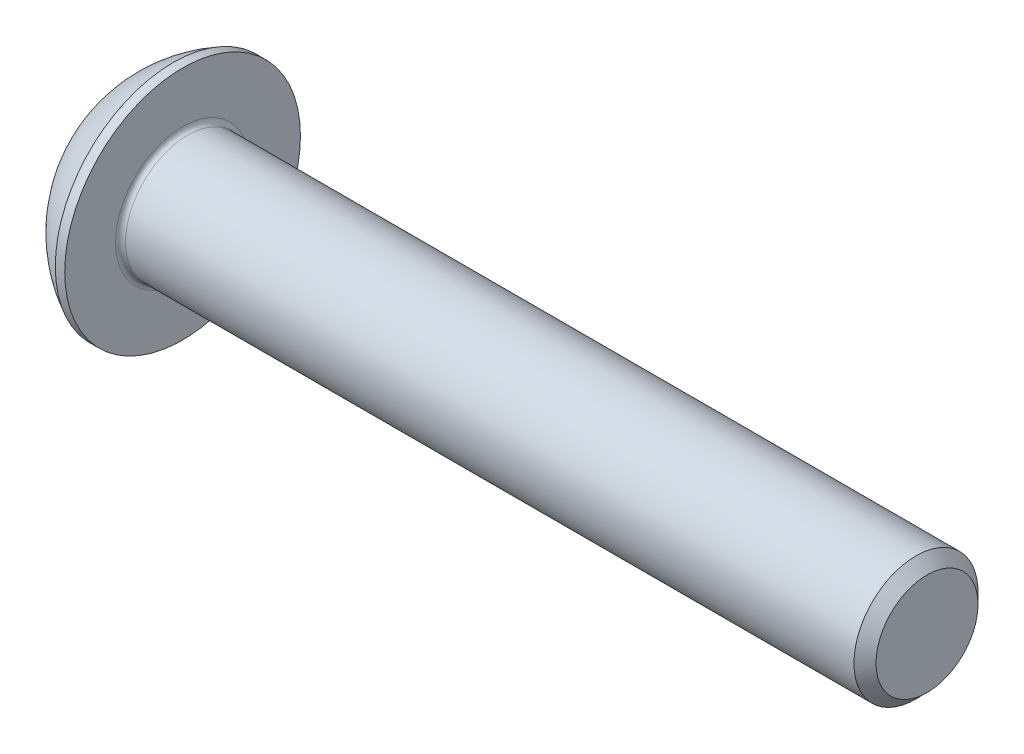
SolidWorks part; units mm, degrees
ref_plane "Plane1" through (0, 0, 0) normal (0, 0, 1) x (1, 0, 0)
ref_plane "Plane2" through (0, 0, 0) normal (0, 1, 0) x (1, 0, 0)
ref_plane "Plane3" through (0, 0, 0) normal (1, 0, 0) x (0, 0, -1)
other "Configuration Table"
sketch "BodySke" plane through (0, 0, 0) normal (0, 0, 1) x (1, 0, 0)
  line L0 (32.75, 0) -> (32.75, 2.055)
  line L1 (32.305, 2.5) -> (2.75, 2.5)
  line L2 (2.75, 2.5) -> (2.75, 4.75)
  line L3 (2.75, 4.75) -> (2.37, 4.75)
  line L4 (0, 0) -> (101.6, 0) construction
  line L5 (2.75, -4.75) -> (2.37, -4.75) construction
  line L6 (55.6768, -2.5) -> (2.75, -2.5) construction
  line L7 (32.75, 0) -> (0, 0)
  line L8 (0, 2.375) -> (0, -2.375) construction
  line L9 (0, 0) -> (0, 2.375)
  line L10 (32.75, 2.055) -> (32.305, 2.5)
  line L11 (32.75, -2.055) -> (32.305, -2.5) construction
  line L12 (3.55, 9.525) -> (3.55, -2.5) construction
  line L13 (2.75, 9.525) -> (2.75, -2.5) construction
  arc A1 (0, 2.375) -> (2.37, 4.75) centre (4.755, 0) cw
  dimension "Diameter" = 5
  dimension "Length" = 30
  dimension "Head_dia" = 9.5
  dimension "D1" = 4.75
  dimension "Head_ht" = 2.75
  dimension "Head_side_ht" = 0.38
  dimension "Minor_dia" = 4.11
  dimension "Body_ch_ang" = 45
  dimension "Advance" = 0.8
  dimension "Thread_nom" = 30
revolve "BaseBody" add sketch "BodySke" angle 360 about L4
cosmetic thread "ThreadCosmetic" [suppressed] parameters "Thread_length"=28.4, "Thread_minor"=4.11
fillet "Fillet1" radius 0.2 1 edges at (2.75, 0, 2.5)
sketch "Sketch2" plane through (0, 0, 0) normal (0, 0, 1) x (1, 0, 0)
  line L0 (0, 1.5) -> (1.56, 1.5)
  line L1 (1.56, 1.5) -> (2.426, 0)
  line L3 (2.426, 0) -> (0, 0)
  line L4 (0, 0) -> (0, 1.5)
  line L5 (0, -1.5) -> (1.56, -1.5) construction
  line L6 (0, 0) -> (47.625, 0) construction
  dimension "D2" = 60
  dimension "PreBroach_depth" = 1.56
  dimension "PreBroach_dia" = 3
revolve "PreBroach" cut sketch "Sketch2" angle 360 about L6
sketch "Sketch3" plane through (0, 0, 0) normal (1, 0, 0) x (0, 0, -1)
  line L0 (-1.5, -0.866) -> (-1.5, 0.866)
  line L1 (-1.5, 0.866) -> (0, 1.7321)
  line L2 (0, 1.7321) -> (1.5, 0.866)
  line L3 (1.5, 0.866) -> (1.5, -0.866)
  line L4 (1.5, -0.866) -> (0, -1.7321)
  line L5 (0, -1.7321) -> (-1.5, -0.866)
  dimension "Hex_size" = 3
  dimension "D3" = 3
  dimension "D1" = 1.5
  dimension "D2" = 1.5
extrude "Hex" cut sketch "Sketch3" along normal blind 1.56
sketch "ThdSchSke" plane through (0, 0, 0) normal (0, 0, 1) x (1, 0, 0)
  line L0 (4.35, -2.055) -> (4.0384, -2.5)
  line L1 (4.35, -2.055) -> (4.6616, -2.5)
  line L2 (4.6616, -2.5) -> (4.6616, -3.125)
  line L3 (-3.175, 0) -> (5.1513, 0) construction
  line L5 (4.6616, -3.125) -> (4.0384, -3.125)
  line L6 (4.0384, -3.125) -> (4.0384, -2.5)
  dimension "Diameter" = 5
  dimension "Thread_minor" = 4.11
  dimension "SideAngle" = 55
  dimension "VeeAngle" = 70
  dimension "Overcut" = 6.25
  dimension "Start" = 4.35
revolve "ThreadSchematic" [suppressed] cut sketch "ThdSchSke" angle 360 about L3
pattern_linear "ThdSchPat" [suppressed]
equation "\"D1@BodySke\" = \"Head_dia@BodySke\" * .5"
equation "\"Thread_minor@ThreadCosmetic\" = \"Minor_dia@BodySke\""
equation "\"D1@Sketch3\" = \"Hex_size@Sketch3\" / 2"
equation "\"D2@Sketch3\" = \"D1@Sketch3\""
equation "\"D3@Sketch3\" = \"Hex_size@Sketch3\""
equation "\"Thread_length@ThreadCosmetic\" = ((sgn( (\"Length@BodySke\" - \"Advance@BodySke\" * 2.0) - \"Thread_nom@BodySke\" )-1)*( (\"Length@BodySke\" - \"Advance@BodySke\" * 2.0) - \"Thread_nom@BodySke\" ))/-2+ \"Thread_nom@BodySke\""
equation "\"Thread_minor@ThdSchSke\" = \"Minor_dia@BodySke\""
equation "\"Diameter@ThdSchSke\" = \"Diameter@BodySke\""
equation "\"Overcut@ThdSchSke\" = \"Diameter@BodySke\" * 1.25"
equation "\"Start@ThdSchSke\" = \"Head_ht@BodySke\" + \"Length@BodySke\" - \"Thread_length@ThreadCosmetic\"  '---Non-countersunk---"
equation "\"Num_threads@ThdSchPat\" = int( \"Thread_length@ThreadCosmetic\" / \"Advance@BodySke\" + 0.999 )  + 1"
equation "\"Advance@ThdSchPat\" = \"Thread_length@ThreadCosmetic\" /  (\"Num_threads@ThdSchPat\" - 1) 'relax it"
equation "\"Num_threads@ThdSchPat\" = \"Num_threads@ThdSchPat\" - sgn( \"Num_threads@ThdSchPat\" - 1) '---chamfered tips only---"
